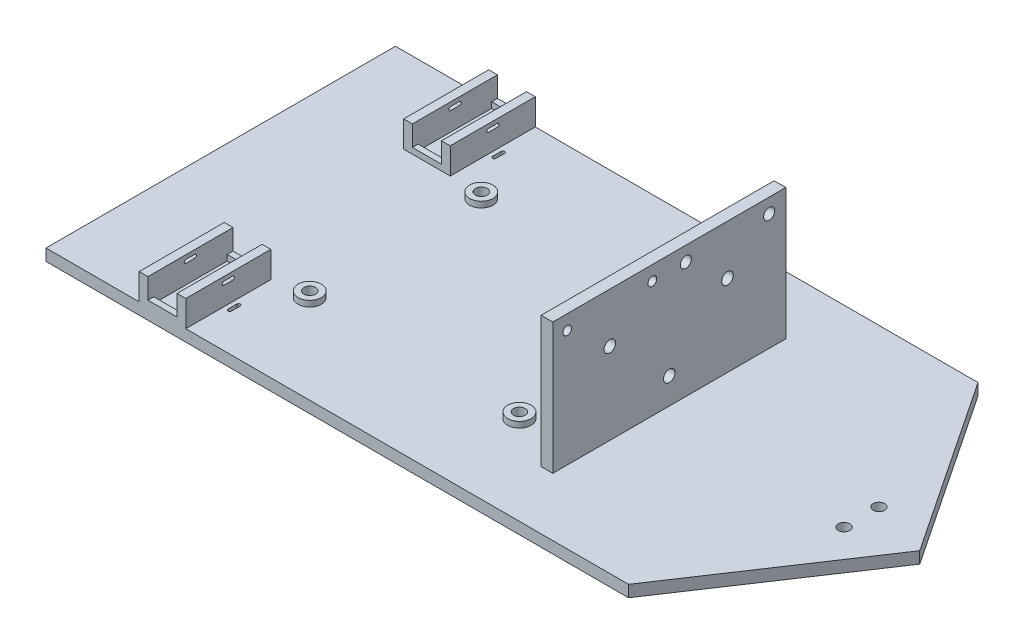
SolidWorks part; units mm, degrees
ref_plane "Front Plane" through (0, 0, 0) normal (0, 0, 1) x (1, 0, 0)
ref_plane "Top Plane" through (0, 0, 0) normal (0, 1, 0) x (1, 0, 0)
ref_plane "Right Plane" through (0, 0, 0) normal (1, 0, 0) x (0, 0, -1)
sketch "Sketch1" plane through (0, 0, 0) normal (0, 1, 0) x (1, 0, 0)
  line L0 (0, 76.2) -> (491.7281, 76.2) construction
  line L1 (0, 0) -> (254, 0)
  line L2 (0, 0) -> (0, 152.4)
  line L3 (0, 152.4) -> (254, 152.4)
  line L5 (254, 152.4) -> (304.8, 76.2)
  line L6 (304.8, 76.2) -> (254, 0)
  dimension "D1" = 152.4
  dimension "D2" = 254
  dimension "D3" = 304.8
extrude "Boss-Extrude1" add sketch "Sketch1" along normal blind 5.08
sketch "Sketch2" plane through (0, 5.08, 0) normal (0, 1, 0) x (1, 0, 0)
  line L0 (0, 76.2) -> (299.9222, 76.2) construction
  line L1 (0, 152.4) -> (0, 0) construction
  circle A0 centre (76.2, 38.7985) radius 2.54
  circle A1 centre (167.64, 38.7985) radius 2.54
  circle A2 centre (167.64, 113.6015) radius 2.54
  circle A3 centre (76.2, 113.6015) radius 2.54
  dimension "D1" = 5.08
  dimension "D3" = 5.08
  dimension "D2" = 76.2
  dimension "D4" = 91.44
  dimension "D5" = 37.4015
extrude "Cut-Extrude1" cut sketch "Sketch2" against normal through all
sketch "Sketch3" plane through (0, 5.08, 0) normal (0, 1, 0) x (1, 0, 0)
  line L0 (0, 76.2) -> (328.5543, 76.2) construction
  line L1 (0, 152.4) -> (0, 0) construction
  circle A0 centre (279.4, 68.58) radius 2.54
  circle A1 centre (279.4, 83.82) radius 2.54
  dimension "D1" = 5.08
  dimension "D2" = 279.4
  dimension "D3" = 7.62
extrude "Cut-Extrude2" cut sketch "Sketch3" against normal through all
sketch "Sketch4" plane through (0, 5.08, 0) normal (0, 1, 0) x (1, 0, 0)
  line L0 (50.8, 0) -> (50.8, 152.4) construction
  line L1 (40.64, 0) -> (44.45, 0)
  line L2 (40.64, 0) -> (40.64, 37.084)
  line L3 (40.64, 37.084) -> (44.45, 37.084)
  line L4 (44.45, 0) -> (44.45, 37.084)
  line L5 (0, 0) -> (254, 0) construction
  line L6 (254, 152.4) -> (0, 152.4) construction
  line L7 (57.15, 0) -> (57.15, 37.084)
  line L8 (60.96, 37.084) -> (57.15, 37.084)
  line L9 (60.96, 0) -> (60.96, 37.084)
  line L10 (60.96, 0) -> (57.15, 0)
  line L11 (0, 76.2) -> (304.8, 76.2) construction
  line L12 (0, 152.4) -> (0, 0) construction
  line L13 (254, 0) -> (304.8, 76.2) construction
  line L14 (60.96, 152.4) -> (57.15, 152.4)
  line L15 (60.96, 152.4) -> (60.96, 115.316)
  line L16 (60.96, 115.316) -> (57.15, 115.316)
  line L17 (57.15, 152.4) -> (57.15, 115.316)
  line L18 (44.45, 152.4) -> (44.45, 115.316)
  line L19 (40.64, 115.316) -> (44.45, 115.316)
  line L20 (40.64, 152.4) -> (40.64, 115.316)
  line L21 (40.64, 152.4) -> (44.45, 152.4)
  dimension "D1" = 50.8
  dimension "D2" = 6.35
  dimension "D3" = 3.81
  dimension "D4" = 37.084
  dimension "D5" = 40.64
extrude "Boss-Extrude2" add sketch "Sketch4" along normal blind 11.43
sketch "Sketch5" plane through (0, 5.08, 0) normal (0, 1, 0) x (1, 0, 0)
  line L0 (57.15, 37.084) -> (57.15, 0) construction
  line L1 (44.45, 0) -> (57.15, 0)
  line L2 (44.45, 0) -> (44.45, 2.54)
  line L3 (44.45, 2.54) -> (57.15, 2.54)
  line L4 (57.15, 0) -> (57.15, 2.54)
  line L5 (0, 76.2) -> (304.8, 76.2) construction
  line L6 (0, 152.4) -> (0, 0) construction
  line L7 (57.15, 152.4) -> (57.15, 149.86)
  line L8 (44.45, 149.86) -> (57.15, 149.86)
  line L9 (44.45, 152.4) -> (44.45, 149.86)
  line L10 (44.45, 152.4) -> (57.15, 152.4)
  line L11 (57.15, 115.316) -> (57.15, 117.856)
  line L12 (44.45, 37.084) -> (57.15, 37.084)
  line L13 (44.45, 37.084) -> (44.45, 34.544)
  line L14 (44.45, 34.544) -> (57.15, 34.544)
  line L15 (57.15, 37.084) -> (57.15, 34.544)
  line L16 (44.45, 117.856) -> (57.15, 117.856)
  line L17 (44.45, 115.316) -> (44.45, 117.856)
  line L18 (44.45, 115.316) -> (57.15, 115.316)
  dimension "D1" = 2.54
  dimension "D2" = 2.54
extrude "Boss-Extrude3" add sketch "Sketch5" along normal blind 2.54
sketch "Sketch6" plane through (0, 5.08, 0) normal (0, 1, 0) x (1, 0, 0)
  line L0 (0, 76.2) -> (304.8, 76.2) construction
  line L1 (0, 152.4) -> (0, 0) construction
  line L2 (76.2, 38.7985) -> (167.64, 38.7985) construction
  line L3 (76.2, 113.6015) -> (167.64, 113.6015) construction
  line L6 (121.92, 113.6015) -> (121.92, 38.7985) construction
  circle A0 centre (76.2, 38.7985) radius 2.54
  circle A1 centre (76.2, 38.7985) radius 5.08
  circle A2 centre (167.64, 38.7985) radius 2.54
  circle A3 centre (167.64, 38.7985) radius 5.08
  circle A4 centre (167.64, 113.6015) radius 2.54
  circle A5 centre (167.64, 113.6015) radius 5.08
  circle A6 centre (76.2, 113.6015) radius 2.54
  circle A7 centre (76.2, 113.6015) radius 5.08
  dimension "D1" = 5.08
  dimension "D2" = 10.16
extrude "Boss-Extrude4" add sketch "Sketch6" along normal blind 2.54
sketch "Sketch7" plane through (0, 5.08, 0) normal (0, 1, 0) x (1, 0, 0)
  line L0 (0, 76.2) -> (304.8, 76.2) construction
  line L1 (190.5, 127) -> (195.58, 127)
  line L2 (190.5, 127) -> (190.5, 25.4)
  line L3 (190.5, 25.4) -> (195.58, 25.4)
  line L4 (195.58, 127) -> (195.58, 25.4)
  line L5 (0, 152.4) -> (0, 0) construction
  point P9 (190.5, 76.2)
  dimension "D1" = 5.08
  dimension "D2" = 101.6
  dimension "D3" = 190.5
extrude "Boss-Extrude5" add sketch "Sketch7" along normal blind 57.15
sketch "Sketch8" plane through (195.58, 0, 0) normal (1, 0, 0) x (0, 0, -1)
  line L0 (25.4, 62.23) -> (25.4, 5.08) construction
  line L2 (31.75, 55.88) -> (68.834, 55.88) construction
  line L3 (50.292, 55.88) -> (50.292, 62.23) construction
  line L4 (25.4, 62.23) -> (127, 62.23) construction
  circle A0 centre (31.75, 55.88) radius 1.905
  circle A1 centre (68.834, 55.88) radius 1.905
  circle A2 centre (50.292, 40.64) radius 2.54
  dimension "D1" = 3.81
  dimension "D4" = 3.81
  dimension "D6" = 5.08
  dimension "D2" = 6.35
  dimension "D3" = 50.8
  dimension "D5" = 37.084
  dimension "D7" = 15.24
extrude "Cut-Extrude3" cut sketch "Sketch8" against normal up to next
sketch "Sketch10" plane through (195.58, 0, 0) normal (1, 0, 0) x (0, 0, -1)
  line L0 (76.2, 62.23) -> (76.2, 5.08) construction
  line L1 (25.4, 62.23) -> (127, 62.23) construction
  line L2 (0, 16.51) -> (152.4, 16.51) construction
  circle A0 centre (76.2, 16.51) radius 2.54
  dimension "D1" = 5.08
extrude "Cut-Extrude5" cut sketch "Sketch10" against normal up to next
sketch "Sketch12" plane through (40.64, 0, 0) normal (-1, 0, 0) x (0, 0, 1)
  line L0 (-20.447, 13.97) -> (-16.637, 13.97) construction
  line L1 (-20.447, 14.732) -> (-16.637, 14.732)
  line L2 (-20.447, 13.208) -> (-16.637, 13.208)
  line L3 (-37.084, 16.51) -> (0, 16.51) construction
  line L4 (-18.542, 16.51) -> (-18.542, 5.08) construction
  line L5 (-37.084, 5.08) -> (0, 5.08) construction
  arc A0 (-20.447, 14.732) -> (-20.447, 13.208) centre (-20.447, 13.97) ccw
  arc A1 (-16.637, 13.208) -> (-16.637, 14.732) centre (-16.637, 13.97) ccw
  point P2 (-18.542, 13.97)
  dimension "D2" = 0.762
  dimension "D1" = 2.54
  dimension "D3" = 1.905
extrude "Cut-Extrude7" cut sketch "Sketch12" against normal blind 25.4
sketch "Sketch13" plane through (40.64, 0, 0) normal (-1, 0, 0) x (0, 0, 1)
  line L0 (-135.763, 13.97) -> (-131.953, 13.97) construction
  line L1 (-135.763, 14.732) -> (-131.953, 14.732)
  line L2 (-135.763, 13.208) -> (-131.953, 13.208)
  line L3 (-133.858, 16.51) -> (-133.858, 5.08) construction
  line L4 (-152.4, 16.51) -> (-115.316, 16.51) construction
  line L5 (-152.4, 5.08) -> (-115.316, 5.08) construction
  arc A0 (-135.763, 14.732) -> (-135.763, 13.208) centre (-135.763, 13.97) ccw
  arc A1 (-131.953, 13.208) -> (-131.953, 14.732) centre (-131.953, 13.97) ccw
  point P2 (-133.858, 13.97)
  point P13 (0, 0)
  dimension "D1" = 0.762
  dimension "D2" = 2.54
  dimension "D3" = 1.905
extrude "Cut-Extrude8" cut sketch "Sketch13" against normal blind 25.4
sketch "Sketch14" plane through (0, 5.08, 0) normal (0, 1, 0) x (1, 0, 0)
  line L0 (50.8, 0) -> (50.8, 152.4) construction
  line L1 (44.45, 0) -> (57.15, 0) construction
  line L2 (57.15, 152.4) -> (44.45, 152.4) construction
  line L3 (40.64, 37.084) -> (40.64, 0) construction
  line L4 (40.64, 18.542) -> (60.96, 18.542) construction
  line L5 (60.96, 0) -> (60.96, 37.084) construction
  line L6 (40.64, 18.542) -> (0, 18.542) construction
  line L7 (0, 152.4) -> (0, 0) construction
  line L8 (38.1, 16.637) -> (38.1, 20.447) construction
  line L9 (37.338, 16.637) -> (37.338, 20.447)
  line L10 (38.862, 16.637) -> (38.862, 20.447)
  line L11 (63.5, 16.637) -> (63.5, 20.447) construction
  line L12 (64.262, 16.637) -> (64.262, 20.447)
  line L13 (62.738, 16.637) -> (62.738, 20.447)
  line L14 (0, 76.2) -> (304.8, 76.2) construction
  line L15 (38.1, 135.763) -> (38.1, 131.953) construction
  line L16 (37.338, 135.763) -> (37.338, 131.953)
  line L17 (38.862, 135.763) -> (38.862, 131.953)
  line L18 (63.5, 135.763) -> (63.5, 131.953) construction
  line L19 (64.262, 135.763) -> (64.262, 131.953)
  line L20 (62.738, 135.763) -> (62.738, 131.953)
  arc A0 (37.338, 16.637) -> (38.862, 16.637) centre (38.1, 16.637) ccw
  arc A1 (38.862, 20.447) -> (37.338, 20.447) centre (38.1, 20.447) ccw
  arc A2 (64.262, 16.637) -> (62.738, 16.637) centre (63.5, 16.637) cw
  arc A3 (62.738, 20.447) -> (64.262, 20.447) centre (63.5, 20.447) cw
  arc A4 (37.338, 135.763) -> (38.862, 135.763) centre (38.1, 135.763) cw
  arc A5 (38.862, 131.953) -> (37.338, 131.953) centre (38.1, 131.953) cw
  arc A6 (64.262, 135.763) -> (62.738, 135.763) centre (63.5, 135.763) ccw
  arc A7 (62.738, 131.953) -> (64.262, 131.953) centre (63.5, 131.953) ccw
  point P17 (38.1, 18.542)
  point P25 (63.5, 18.542)
  point P34 (38.1, 133.858)
  point P41 (63.5, 133.858)
  dimension "D1" = 0.762
  dimension "D2" = 1.905
  dimension "D3" = 2.54
extrude "Cut-Extrude9" cut sketch "Sketch14" against normal through all
sketch "Sketch15" plane through (195.58, 0, 0) normal (1, 0, 0) x (0, 0, -1)
  line L0 (68.834, 55.88) -> (127, 55.88) construction
  line L1 (127, 62.23) -> (127, 5.08) construction
  line L2 (50.292, 40.64) -> (127, 40.64) construction
  line L3 (25.4, 62.23) -> (127, 62.23) construction
  line L4 (76.2, 62.23) -> (76.2, 5.08) construction
  line L5 (25.4, 5.08) -> (127, 5.08) construction
  line L6 (76.2, 5.08) -> (127, 5.08) construction
  line L7 (101.6, 5.08) -> (101.6, 62.23) construction
  circle A0 centre (83.4136, 55.88) radius 2.413
  circle A1 centre (119.7864, 55.88) radius 2.413
  circle A3 centre (101.6, 40.64) radius 2.54
  point P24 (0, 0)
  point P25 (0, 0)
  dimension "D1" = 4.826
  dimension "D3" = 5.08
  dimension "D2" = 18.1864
extrude "Cut-Extrude10" cut sketch "Sketch15" against normal through all
